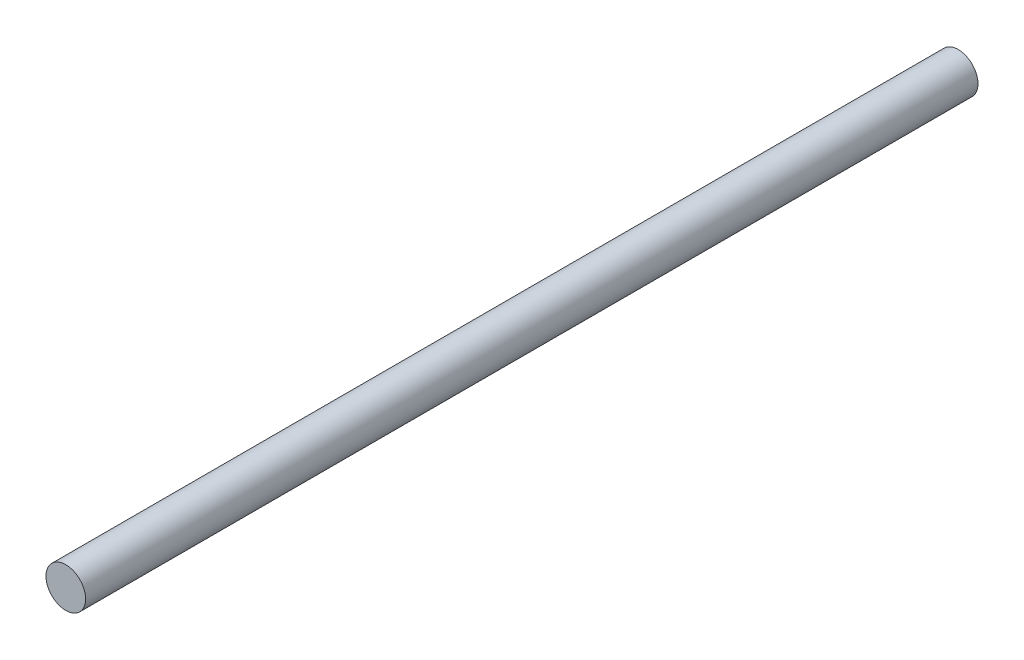
SolidWorks part; units mm, degrees
material "Acero al carbono no aleado"
ref_plane "Alzado" through (0, 0, 0) normal (0, 0, 1) x (1, 0, 0)
ref_plane "Planta" through (0, 0, 0) normal (0, 1, 0) x (1, 0, 0)
ref_plane "Vista lateral" through (0, 0, 0) normal (1, 0, 0) x (0, 0, -1)
sketch "Croquis1" plane through (0, 0, 0) normal (0, 0, 1) x (1, 0, 0)
  circle A0 centre (0, 0) radius 10
  dimension "D1" = 20
extrude "Saliente-Extruir1" add sketch "Croquis1" along normal mid plane 450
